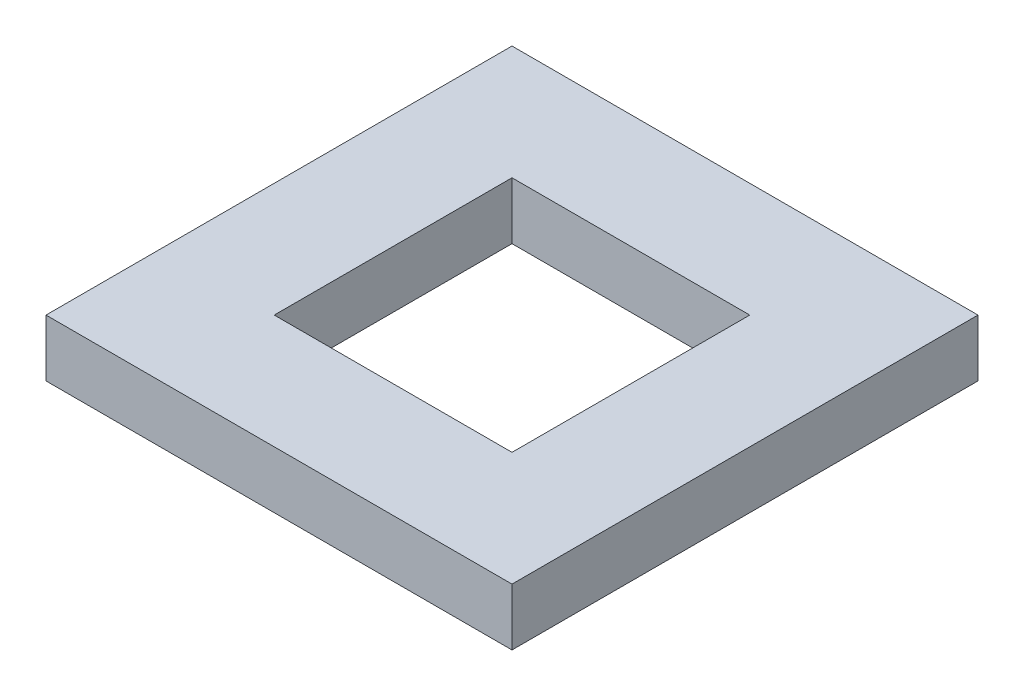
SolidWorks part; units mm, degrees
material "Резина"
ref_plane "Спереди" through (0, 0, 0) normal (0, 0, 1) x (1, 0, 0)
ref_plane "Сверху" through (0, 0, 0) normal (0, 1, 0) x (1, 0, 0)
ref_plane "Справа" through (0, 0, 0) normal (1, 0, 0) x (0, 0, -1)
sketch "Эскиз2" plane through (0, 0, 0) normal (0, 1, 0) x (1, 0, 0)
  line L0 (0, 0) -> (24.5, 0)
  line L1 (0, 0) -> (0, 24.5)
  line L2 (24.5, 0) -> (24.5, 24.5)
  line L3 (0, 24.5) -> (24.5, 24.5)
  line L4 (6, 6) -> (18.5, 6)
  line L5 (6, 6) -> (6, 18.5)
  line L6 (18.5, 6) -> (18.5, 18.5)
  line L7 (6, 18.5) -> (18.5, 18.5)
  line L8 (12.25, 24.5) -> (12.25, 0) construction
  line L9 (24.5, 12.25) -> (0, 12.25) construction
  line L10 (12.25, 18.5) -> (12.25, 6) construction
  line L11 (18.5, 12.25) -> (6, 12.25) construction
  dimension "D1" = 24.5
  dimension "D2" = 24.5
  dimension "D3" = 12.5
  dimension "D4" = 12.5
extrude "Бобышка-Вытянуть1" add sketch "Эскиз2" along normal blind 3
